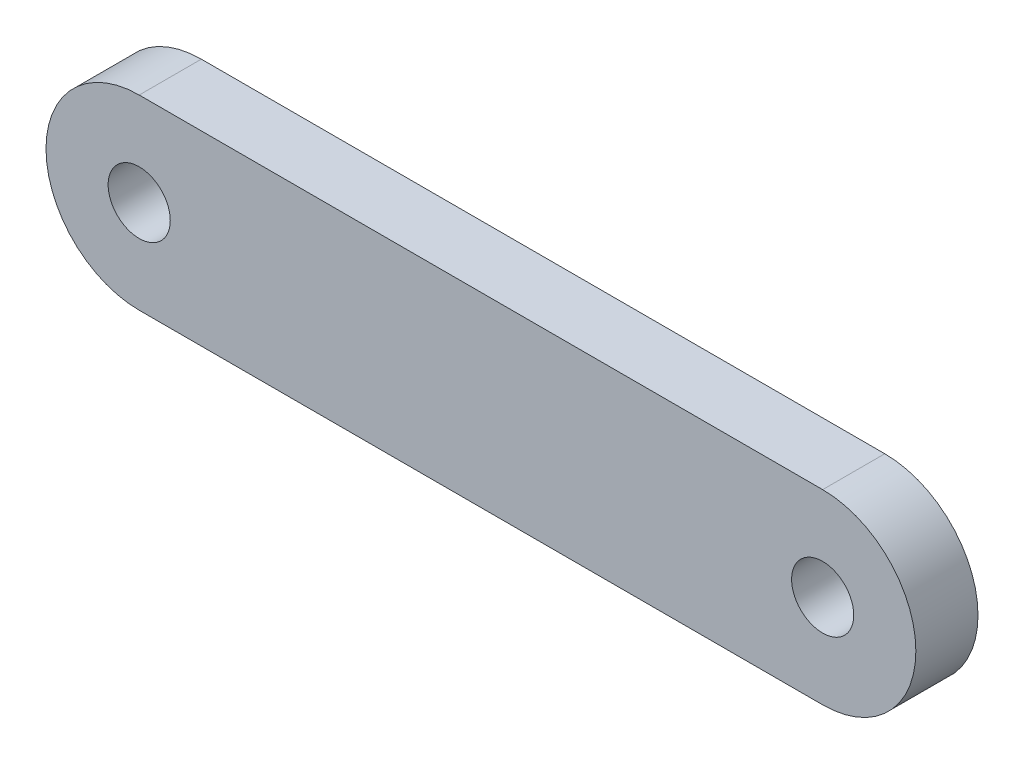
SolidWorks part; units mm, degrees
ref_plane "Front Plane" through (0, 0, 0) normal (0, 0, 1) x (1, 0, 0)
ref_plane "Top Plane" through (0, 0, 0) normal (0, 1, 0) x (1, 0, 0)
ref_plane "Right Plane" through (0, 0, 0) normal (1, 0, 0) x (0, 0, -1)
sketch "Sketch1" plane through (0, 0, 0) normal (0, 0, 1) x (1, 0, 0)
  line L0 (-55, 0) -> (55, 0) construction
  line L1 (-55, 15) -> (55, 15)
  line L2 (-55, -15) -> (55, -15)
  arc A0 (-55, 15) -> (-55, -15) centre (-55, 0) ccw
  arc A1 (55, -15) -> (55, 15) centre (55, 0) ccw
  circle A2 centre (-55, 0) radius 5
  circle A3 centre (55, 0) radius 5
  point P2 (0, 0)
  point P12 (0, -15)
  dimension "D1" = 10
  dimension "D2" = 10
  dimension "D3" = 110
  dimension "D4" = 30
extrude "Boss-Extrude1" add sketch "Sketch1" along normal blind 10
